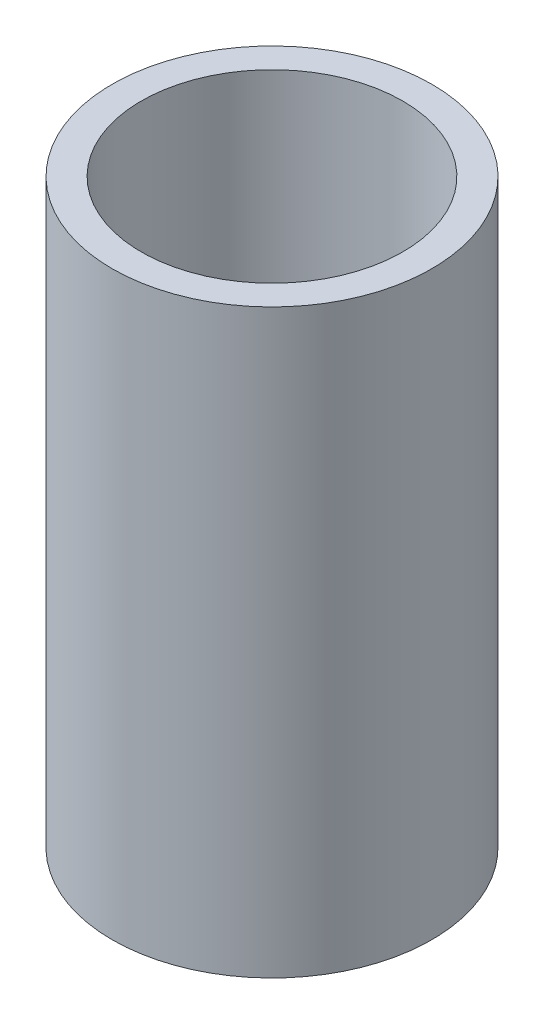
SolidWorks part; units mm, degrees
ref_plane "Спереди" through (0, 0, 0) normal (0, 0, 1) x (1, 0, 0)
ref_plane "Сверху" through (0, 0, 0) normal (0, 1, 0) x (1, 0, 0)
ref_plane "Справа" through (0, 0, 0) normal (1, 0, 0) x (0, 0, -1)
sketch "Эскиз1" plane through (0, 0, 0) normal (0, 0, 1) x (1, 0, 0)
  line L0 (0, -110.6031) -> (0, 130.0787) construction
  line L1 (45, 100) -> (55, 100)
  line L2 (45, 100) -> (45, -100)
  line L3 (45, -100) -> (55, -100)
  line L4 (55, 100) -> (55, -100)
  point P4 (45, 0)
  dimension "D1" = 10
  dimension "D2" = 200
  dimension "D3" = 45
revolve "Повернуть1" add sketch "Эскиз1" angle 360 about L0
surface "Поверхность-Промежуточная поверхность1" parameters "D0"=10000
surface "Поверхность-Промежуточная поверхность2" parameters "D0"=50000
